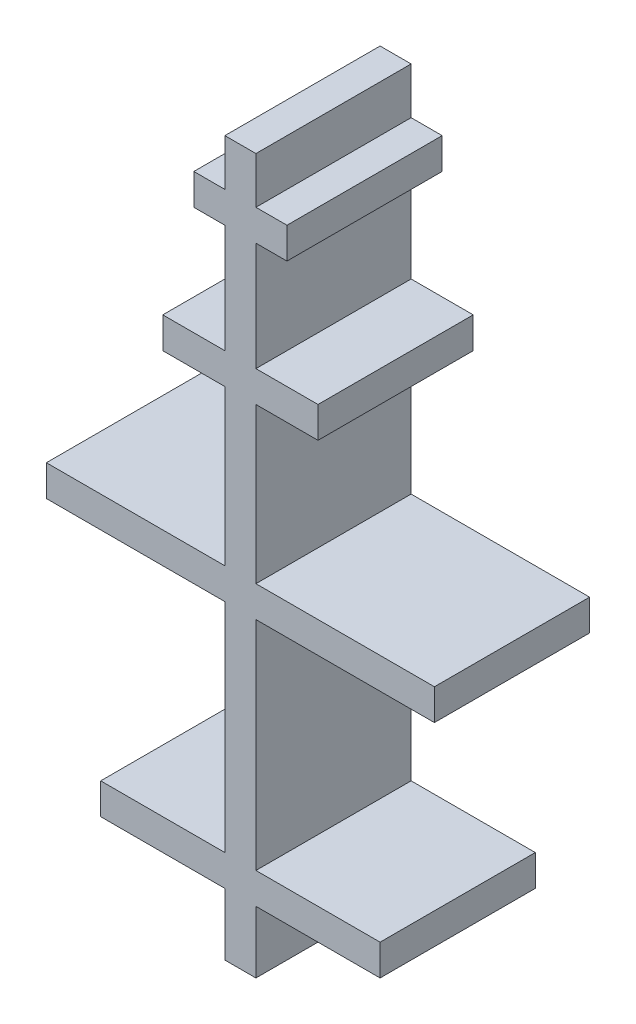
SolidWorks part; units mm, degrees
material "Papel canelado"
ref_plane "Plano frontal" through (0, 0, 0) normal (0, 0, 1) x (1, 0, 0)
ref_plane "Plano superior" through (0, 0, 0) normal (0, 1, 0) x (1, 0, 0)
ref_plane "Plano direito" through (0, 0, 0) normal (1, 0, 0) x (0, 0, -1)
sketch "Esboço1" plane through (0, 0, 0) normal (0, 0, 1) x (1, 0, 0)
  line L0 (10, 215) -> (20, 215)
  line L1 (0, 0) -> (10, 0)
  line L2 (0, 0) -> (0, 20)
  line L3 (0, 230) -> (10, 230)
  line L4 (10, 0) -> (10, 20)
  line L5 (-57.5, 110) -> (0, 110)
  line L6 (-57.5, 110) -> (-57.5, 100)
  line L7 (-57.5, 100) -> (0, 100)
  line L8 (67.5, 110) -> (67.5, 100)
  line L9 (-40, 30) -> (0, 30)
  line L10 (-40, 30) -> (-40, 20)
  line L11 (-40, 20) -> (0, 20)
  line L12 (50, 30) -> (50, 20)
  line L13 (-20, 170) -> (0, 170)
  line L14 (-20, 170) -> (-20, 160)
  line L15 (-20, 160) -> (0, 160)
  line L16 (30, 170) -> (30, 160)
  line L17 (-10, 215) -> (0, 215)
  line L18 (-10, 215) -> (-10, 205)
  line L19 (-10, 205) -> (0, 205)
  line L20 (20, 215) -> (20, 205)
  line L21 (10, 205) -> (20, 205)
  line L22 (0, 215) -> (0, 230)
  line L23 (10, 215) -> (10, 230)
  line L24 (10, 170) -> (30, 170)
  line L25 (10, 160) -> (30, 160)
  line L26 (0, 170) -> (0, 205)
  line L27 (10, 170) -> (10, 205)
  line L28 (10, 110) -> (67.5, 110)
  line L29 (10, 100) -> (67.5, 100)
  line L30 (0, 110) -> (0, 160)
  line L31 (10, 110) -> (10, 160)
  line L32 (10, 30) -> (50, 30)
  line L33 (10, 20) -> (50, 20)
  line L34 (0, 30) -> (0, 100)
  line L35 (10, 30) -> (10, 100)
  point P14 (5, 230)
  point P18 (-40, 25)
  point P19 (-57.5, 105)
  point P28 (-74.4447, 210.8224)
  point P31 (-20, 165)
  point P32 (-10, 210)
  dimension "D1" = 230
  dimension "D2" = 10
  dimension "D3" = 25
  dimension "D4" = 80
  dimension "D5" = 90
  dimension "D6" = 125
  dimension "D7" = 50
  dimension "D8" = 30
  dimension "D9" = 60
  dimension "D10" = 45
extrude "Ressalto-extrusão1" add sketch "Esboço1" along normal blind 50
